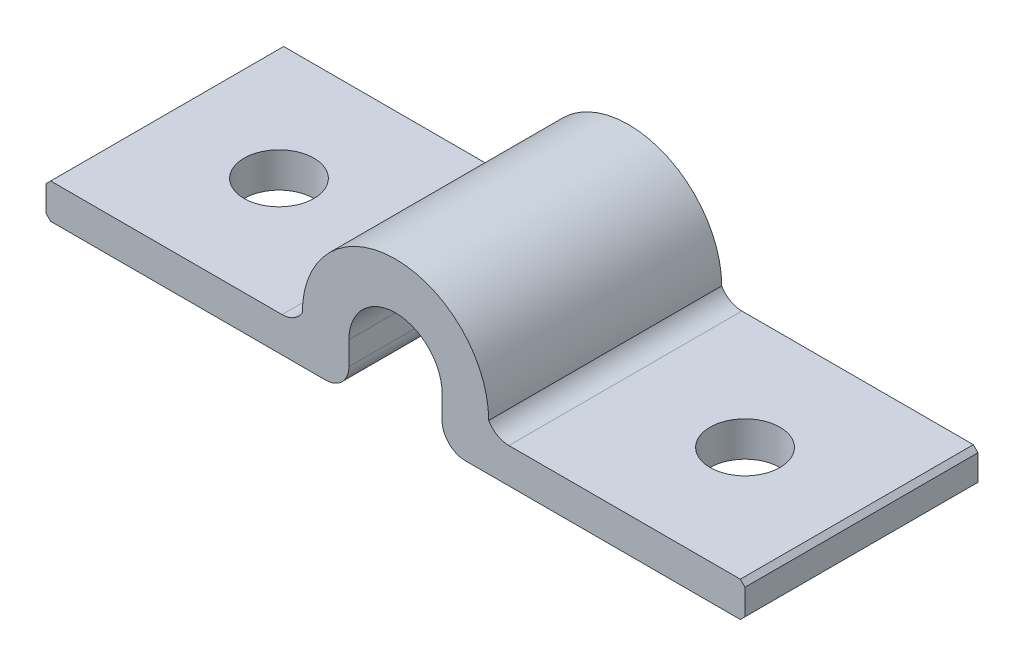
SolidWorks part; units mm, degrees
ref_plane "Front Plane" through (0, 0, 0) normal (0, 0, 1) x (1, 0, 0)
ref_plane "Top Plane" through (0, 0, 0) normal (0, 1, 0) x (1, 0, 0)
ref_plane "Right Plane" through (0, 0, 0) normal (1, 0, 0) x (0, 0, -1)
sketch "Sketch1" plane through (0, 0, 0) normal (0, 0, 1) x (1, 0, 0)
  line L0 (-3, -2) -> (-14.8, -2)
  line L1 (-14.8, -0.5) -> (-15, -0.7)
  line L3 (0, 2) -> (0, 4)
  line L4 (-2, 0) -> (-2, -1)
  line L5 (-4.866, -0.5) -> (-14.8, -0.5)
  line L6 (-15, -0.7) -> (-15, -1.8)
  line L7 (-14.8, -2) -> (-15, -1.8)
  arc A0 (0, 2) -> (-2, 0) centre (0, 0) ccw
  arc A1 (0, 4) -> (-4, 0) centre (0, 0) ccw
  arc A2 (-4.866, -0.5) -> (-4, 0) centre (-4.866, 0.5) ccw
  arc A3 (-2, -1) -> (-3, -2) centre (-3, -1) cw
  point P5 (-15, -2)
  point P13 (-15, -0.5)
  dimension "D1" = 4
  dimension "D2" = 8
  dimension "D5" = 1
  dimension "D6" = 1
  dimension "D3" = 1.5
  dimension "D4" = 15
extrude "Boss-Extrude1" add sketch "Sketch1" along normal blind 10
sketch "Sketch2" plane through (0, -0.5, 0) normal (0, 1, 0) x (1, 0, 0)
  line L0 (-4.866, 0) -> (-14.8, 0) construction
  line L1 (-15, -10) -> (-15, 0) construction
  circle A0 centre (-10, -5) radius 1.5
  dimension "D3" = 3
  dimension "D1" = 5
  dimension "D2" = 5
extrude "Cut-Extrude1" cut sketch "Sketch2" against normal blind 30
mirror "Mirror1" about plane through (0, 2, 10) normal (-1, 0, 0) of "Cut-Extrude1", "Boss-Extrude1"
